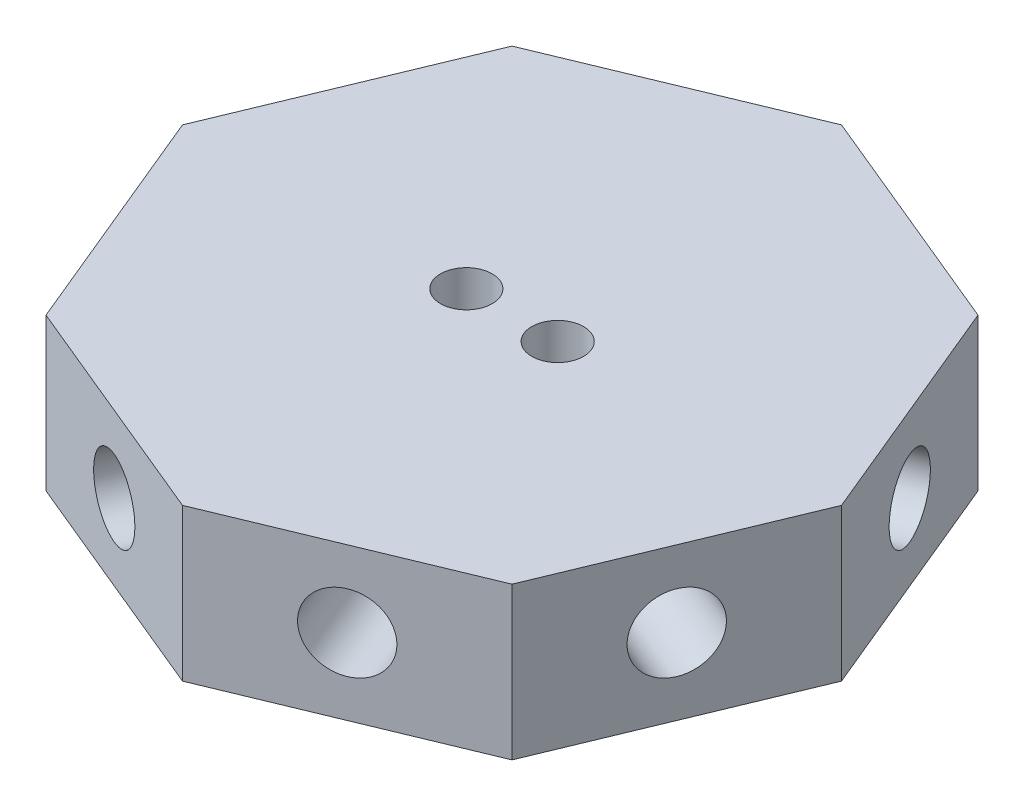
SolidWorks part; units mm, degrees
ref_plane "Front Plane" through (0, 0, 0) normal (0, 0, 1) x (1, 0, 0)
ref_plane "Top Plane" through (0, 0, 0) normal (0, 1, 0) x (1, 0, 0)
ref_plane "Right Plane" through (0, 0, 0) normal (1, 0, 0) x (0, 0, -1)
sketch "Sketch1" plane through (0, 0, 0) normal (0, 1, 0) x (1, 0, 0)
  line L0 (-1.905, 0) -> (1.905, 0) construction
  line L1 (0, 13.7464) -> (-9.7202, 9.7202)
  line L2 (-9.7202, 9.7202) -> (-13.7464, 0)
  line L3 (-13.7464, 0) -> (-9.7202, -9.7202)
  line L4 (-9.7202, -9.7202) -> (0, -13.7464)
  line L5 (0, -13.7464) -> (9.7202, -9.7202)
  line L6 (9.7202, -9.7202) -> (13.7464, 0)
  line L7 (13.7464, 0) -> (9.7202, 9.7202)
  line L8 (9.7202, 9.7202) -> (0, 13.7464)
  circle A0 centre (0, 0) radius 12.7 construction
  circle A1 centre (1.905, 0) radius 1.0795
  circle A2 centre (-1.905, 0) radius 1.0795
  point P13 (0, 0)
  dimension "D1" = 25.4
  dimension "D3" = 2.159
  dimension "D4" = 2.159
  dimension "D2" = 3.81
extrude "Boss-Extrude1" add sketch "Sketch1" along normal blind 6.35
sketch "Sketch2" plane through (-4.8601, 0, 11.7333) normal (-0.3827, 0, 0.9239) x (0.9239, 0, 0.3827)
  line L0 (0, 0) -> (0, 6.35) construction
  line L1 (-5.2605, 0) -> (5.2605, 0) construction
  line L2 (-5.2605, 6.35) -> (5.2605, 6.35) construction
  circle A0 centre (0, 3.175) radius 1.5875
  dimension "D1" = 3.175
extrude "Cut-Extrude1" cut sketch "Sketch2" against normal blind 7.62
pattern_circular "CirPattern1" count 8 over 360 about axis through (0, 0, 0) along (0, 1, 0) of "Cut-Extrude1"
